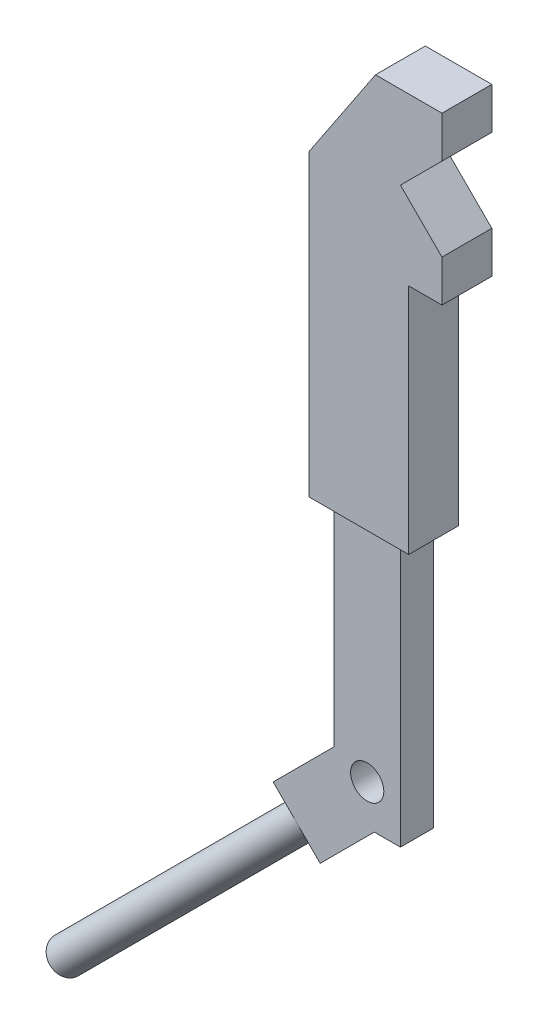
SolidWorks part; units mm, degrees
material "Plain Carbon Steel"
ref_plane "Front Plane" through (0, 0, 0) normal (0, 0, 1) x (1, 0, 0)
ref_plane "Top Plane" through (0, 0, 0) normal (0, 1, 0) x (1, 0, 0)
ref_plane "Right Plane" through (0, 0, 0) normal (1, 0, 0) x (0, 0, -1)
sketch "Sketch1" plane through (0, 0, 0) normal (0, 0, 1) x (1, 0, 0)
  line L1 (-10, 0) -> (10, 0)
  line L2 (-10, 0) -> (-10, 80)
  line L3 (-10, 80) -> (10, 80)
  line L4 (10, 0) -> (10, 80)
  circle A0 centre (0, 12) radius 5
  point P4 (0, 80)
  point P6 (0, 0)
  dimension "D3" = 10
  dimension "D4" = 12
  dimension "D1" = 20
  dimension "D2" = 80
extrude "Boss-Extrude1" add sketch "Sketch1" along normal mid plane 10
sketch "Sketch2" plane through (0, 0, 0) normal (0, 0, 1) x (1, 0, 0)
  line L0 (-15, 80) -> (-15, 170)
  line L1 (-15, 170) -> (5, 200)
  line L7 (15, 150) -> (15, 80)
  line L8 (15, 80) -> (-15, 80)
  line L9 (10, 80) -> (-10, 80) construction
  line L10 (5, 200) -> (25, 200)
  line L11 (25, 200) -> (25, 187.5)
  line L12 (25, 187.5) -> (12.5, 175)
  line L13 (12.5, 175) -> (25, 162.5)
  line L14 (25, 162.5) -> (25, 150)
  line L15 (25, 150) -> (15, 150)
  point P9 (0, 80)
  point P13 (0, 80)
  point P15 (0, 0)
  point P16 (25, 156.25)
  dimension "D1" = 12.5
  dimension "D2" = 30
  dimension "D3" = 70
  dimension "D4" = 30
  dimension "D5" = 20
  dimension "D6" = 40
  dimension "D7" = 12.5
  dimension "D8" = 12.5
  dimension "D9" = 120
  dimension "D10" = 25
extrude "Boss-Extrude2" add sketch "Sketch2" along normal mid plane 15
sketch "Sketch3" plane through (0, 0, 0) normal (0, 0, 1) x (1, 0, 0)
  line L0 (-3.5355, 8.4645) -> (-21.2132, -9.2132) construction
  line L1 (-10, 0) -> (10, 0) construction
  line L2 (-7.0711, 19.0711) -> (-28.2843, -2.1421)
  line L3 (7.0711, 4.9289) -> (-14.1421, -16.2843)
  line L4 (-7.0711, 19.0711) -> (-3.5355, 15.5355)
  line L5 (-28.2843, -2.1421) -> (-14.1421, -16.2843)
  line L6 (3.5355, 8.4645) -> (7.0711, 4.9289)
  line L7 (0, 12) -> (-21.2132, -9.2132) construction
  circle A0 centre (0, 12) radius 5 construction
  arc A1 (-3.5355, 15.5355) -> (3.5355, 8.4645) centre (0, 12) ccw
  dimension "D1" = 45
  dimension "D3" = 10
  dimension "D4" = 10
extrude "Boss-Extrude3" add sketch "Sketch3" along normal mid plane 10
sketch "Sketch4" plane through (-15.2132, -15.2132, 0) normal (-0.7071, -0.7071, 0) x (0, 0, 1)
  circle A0 centre (0, 8.4853) radius 5
extrude "Boss-Extrude4" add sketch "Sketch4" along normal blind 105
